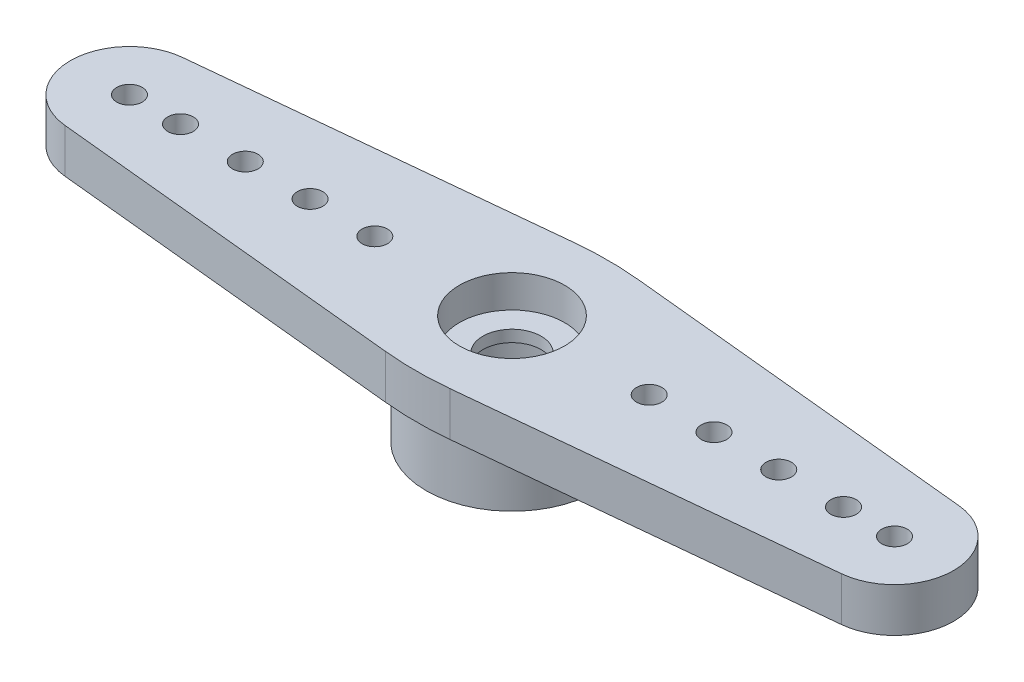
SolidWorks part; units mm, degrees
ref_plane "Front Plane" through (0, 0, 0) normal (0, 0, 1) x (1, 0, 0)
ref_plane "Top Plane" through (0, 0, 0) normal (0, 1, 0) x (1, 0, 0)
ref_plane "Right Plane" through (0, 0, 0) normal (1, 0, 0) x (0, 0, -1)
sketch "Sketch1" plane through (0, 0, 0) normal (0, 1, 0) x (1, 0, 0)
  circle A0 centre (0, 0) radius 3.3655
  circle A1 centre (0, 0) radius 2.5
  dimension "D1" = 6.731
  dimension "D2" = 5
extrude "Boss-Extrude1" add sketch "Sketch1" along normal blind 2.54
sketch "Sketch2" plane through (0, 2.54, 0) normal (0, 1, 0) x (1, 0, 0)
  line L0 (-15, 0) -> (0, 0) construction
  line L1 (0, 0) -> (0, 50000) construction
  line L2 (0, 3.8227) -> (15.2296, 2.3063)
  line L3 (0, -3.8227) -> (15.2296, -2.3063)
  line L4 (0, -3.8227) -> (-15.2296, -2.3063)
  line L5 (0, 3.8227) -> (-15.2296, 2.3063)
  line L9 (15, 0) -> (50000, 0) construction
  circle A0 centre (-10.46, 0) radius 0.5
  circle A1 centre (-7.92, 0) radius 0.5
  circle A2 centre (-5.38, 0) radius 0.5
  circle A3 centre (15, 0) radius 0.5
  arc A4 (15.2296, -2.3063) -> (15.2296, 2.3063) centre (15, 0) ccw
  circle A5 centre (0, 0) radius 3.8227
  arc A6 (-15.2296, -2.3063) -> (-15.2296, 2.3063) centre (-15, 0) cw
  circle A7 centre (5.38, 0) radius 0.5
  circle A8 centre (7.92, 0) radius 0.5
  circle A9 centre (-13, 0) radius 0.5
  circle A10 centre (-15, 0) radius 0.5
  circle A11 centre (0, 0) radius 1.143
  circle A12 centre (10.46, 0) radius 0.5
  circle A13 centre (13, 0) radius 0.5
  dimension "D1" = 15
  dimension "D6" = 4.6355
  dimension "D7" = 7.6454
  dimension "D8" = 2.286
  dimension "D3" = 1
  dimension "D2" = 2
  dimension "D4" = 4
extrude "Boss-Extrude2" add sketch "Sketch2" along normal blind 1.7272
fillet "Fillet1" radius 12.7 2 edges at (0, 3.4036, -3.8227) (0, 3.4036, 3.8227)
sketch "Sketch3" plane through (0, 4.2672, 0) normal (0, 1, 0) x (1, 0, 0)
  circle A0 centre (0, 0) radius 2.0638
  circle M17 centre (0, 0) radius 1.143
  dimension "D1" = 4.1275
extrude "Cut-Extrude1" cut sketch "Sketch3" against normal blind 1.27 contours A0 M17
